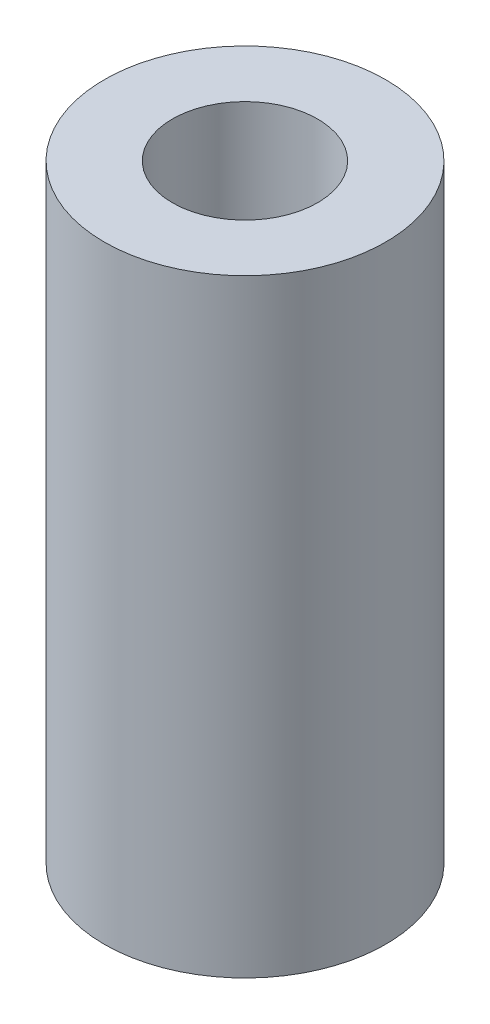
SolidWorks part; units mm, degrees
ref_plane "前视基准面" through (0, 0, 0) normal (0, 0, 1) x (1, 0, 0)
ref_plane "上视基准面" through (0, 0, 0) normal (0, 1, 0) x (1, 0, 0)
ref_plane "右视基准面" through (0, 0, 0) normal (1, 0, 0) x (0, 0, -1)
sketch "草图1" plane through (0, 0, 0) normal (0, 1, 0) x (1, 0, 0)
  circle A0 centre (0, 0) radius 1.6
  circle A1 centre (0, 0) radius 3.1
  dimension "D1" = 3.2
  dimension "D2" = 1.5
extrude "凸台-拉伸1" add sketch "草图1" along normal blind 13.4
